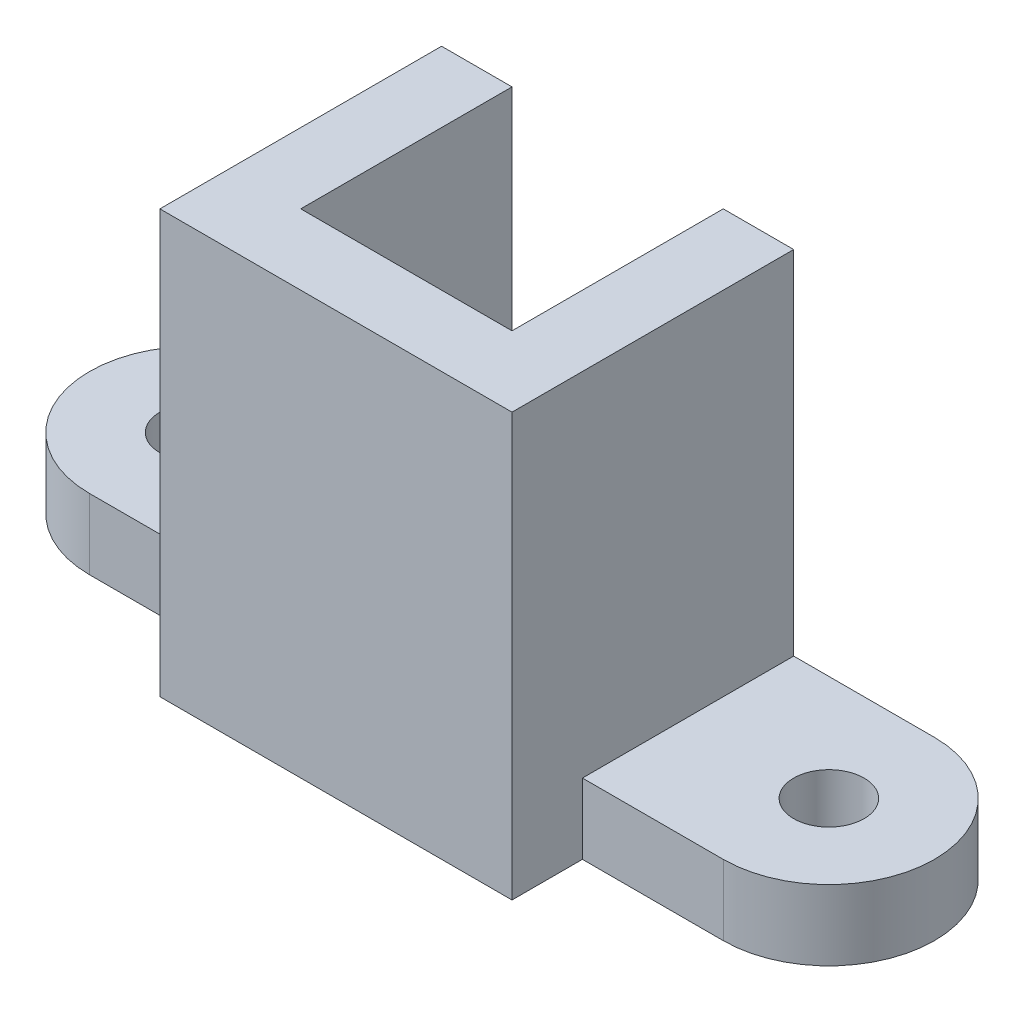
SolidWorks part; units mm, degrees
ref_plane "Front Plane" through (0, 0, 0) normal (0, 0, 1) x (1, 0, 0)
ref_plane "Top Plane" through (0, 0, 0) normal (0, 1, 0) x (1, 0, 0)
ref_plane "Right Plane" through (0, 0, 0) normal (1, 0, 0) x (0, 0, -1)
sketch "Sketch1" plane through (0, 0, 0) normal (0, 1, 0) x (1, 0, 0)
  line L0 (0, -15) -> (20, -15)
  line L10 (20, -15) -> (20, -25)
  line L11 (20, -25) -> (70, -25)
  line L12 (70, -25) -> (70, -15)
  line L13 (70, -15) -> (90, -15)
  line L14 (90, 15) -> (0, 15)
  arc A10 (0, 15) -> (0, -15) centre (0, 0) ccw
  circle A11 centre (0, 0) radius 5
  circle A12 centre (90, 0) radius 5
  arc A13 (90, -15) -> (90, 15) centre (90, 0) ccw
  point P14 (0, 1024.1289)
  dimension "D2" = 15
  dimension "D3" = 10
  dimension "D1" = 90
  dimension "D4" = 50
  dimension "D5" = 10
  dimension "D6" = 20
extrude "Boss-Extrude4" add sketch "Sketch1" along normal blind 10
sketch "Sketch4" plane through (0, 0, 0) normal (0, -1, 0) x (1, 0, 0)
  line L0 (90, -15) -> (0, -15) construction
  line L3 (20, -15) -> (30, -15)
  line L4 (30, 15) -> (30, -15)
  line L6 (30, 15) -> (60, 15)
  line L11 (70, 25) -> (70, -15)
  line L12 (70, -15) -> (60, -15)
  line L13 (60, 15) -> (60, -15)
  line L14 (20, 25) -> (20, -15)
  line L15 (70, 25) -> (20, 25)
  dimension "D1" = 10
  dimension "D2" = 10
extrude "Boss-Extrude6" add sketch "Sketch4" against normal blind 60
sketch "Sketch5" plane through (60, 0, 0) normal (-1, 0, 0) x (0, 0, 1)
  line L0 (-15, 10) -> (15, 60)
  line L1 (15, 60) -> (15, 10)
  line L2 (15, 60) -> (15, 10) construction
  line L3 (-15, 10) -> (15, 10) construction
  line L4 (15, 10) -> (-15, 10)
extrude "Boss-Extrude7" add sketch "Sketch5" along normal blind 30
